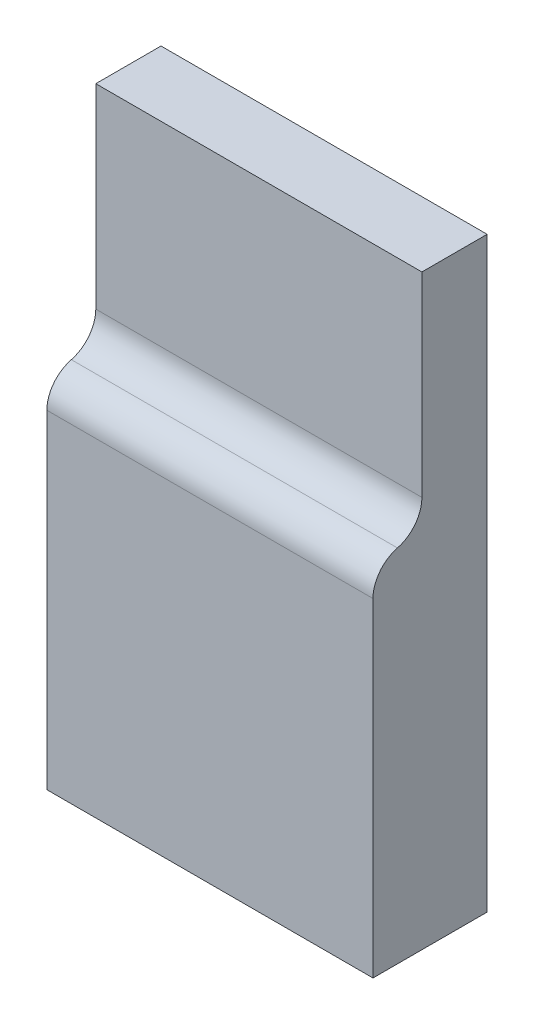
SolidWorks part; units mm, degrees
ref_plane "前视基准面" through (0, 0, 0) normal (0, 0, 1) x (1, 0, 0)
ref_plane "上视基准面" through (0, 0, 0) normal (0, 1, 0) x (1, 0, 0)
ref_plane "右视基准面" through (0, 0, 0) normal (1, 0, 0) x (0, 0, -1)
sketch "草图1" plane through (0, 0, 0) normal (0, 0, 1) x (1, 0, 0)
  line L1 (-50, -90) -> (50, -90)
  line L2 (-50, -90) -> (-50, 90)
  line L3 (-50, 90) -> (50, 90)
  line L4 (50, -90) -> (50, 90)
  line L5 (-50, -90) -> (50, 90) construction
  line L6 (-50, 90) -> (50, -90) construction
  point P0 (0, 0)
  dimension "D1" = 180
  dimension "D2" = 100
extrude "凸台-拉伸1" add sketch "草图1" along normal blind 20
sketch "草图2" plane through (0, 0, 20) normal (0, 0, 1) x (1, 0, 0)
  line L0 (50, -90) -> (50, 90) construction
  line L1 (-50, 20.7726) -> (50, 20.7726)
  line L2 (-50, 20.7726) -> (-50, -90)
  line L3 (-50, -90) -> (50, -90)
  line L4 (50, 20.7726) -> (50, -90)
  line L5 (-50, 20.7726) -> (50, -90) construction
  line L6 (-50, -90) -> (50, 20.7726) construction
  point P0 (0, -34.6137)
extrude "凸台-拉伸2" add sketch "草图2" along normal blind 15
fillet "圆角1" radius 10 1 edges at (0, 20.7726, 35)
fillet "圆角2" radius 10 1 edges at (0, 20.7726, 20)
